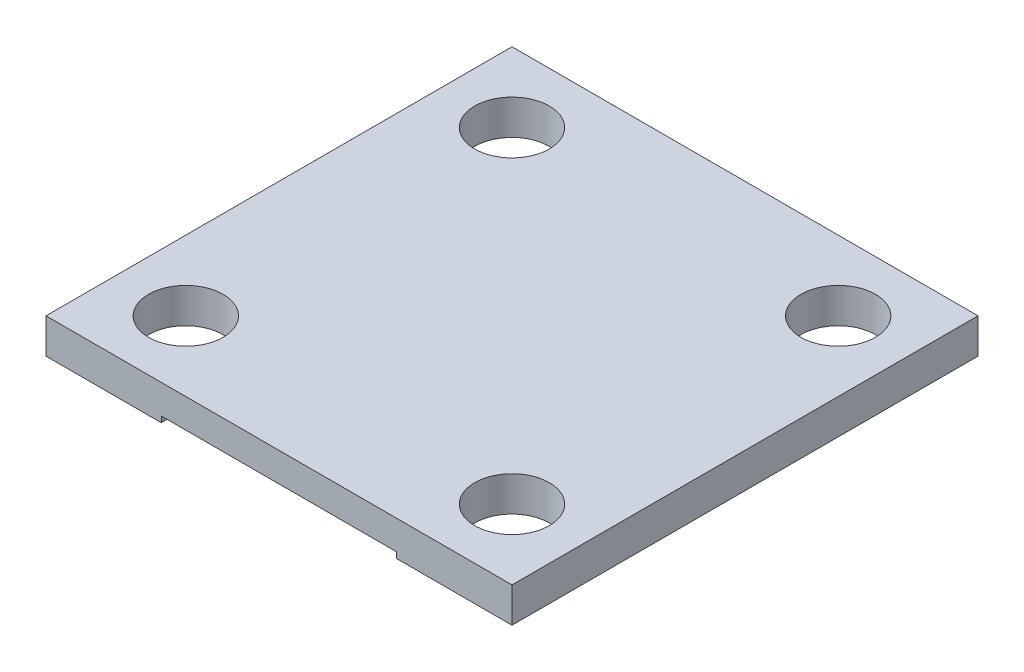
SolidWorks part; units mm, degrees
ref_plane "前视基准面" through (0, 0, 0) normal (0, 0, 1) x (1, 0, 0)
ref_plane "上视基准面" through (0, 0, 0) normal (0, 1, 0) x (1, 0, 0)
ref_plane "右视基准面" through (0, 0, 0) normal (1, 0, 0) x (0, 0, -1)
ref_plane "基准面4" through (0, 0, 0) normal (0, -1, 0) x (1, 0, 0)
sketch "草图1" plane through (0, 0, 0) normal (0, -1, 0) x (1, 0, 0)
  line L0 (10, -10) -> (10, 10)
  line L1 (10, 10) -> (-10, 10)
  line L2 (-10, 10) -> (-10, -10)
  line L3 (-10, -10) -> (10, -10)
extrude "凸台-拉伸1" add sketch "草图1" against normal blind 1.5
sketch "草图2" plane through (0, 0, 0) normal (0, -1, 0) x (1, 0, 0)
  line L0 (-5.05, 10) -> (-5.05, -7.5)
  line L1 (-5.05, -7.5) -> (5.05, -7.5)
  line L2 (5.05, -7.5) -> (5.05, 10)
  line L3 (5.05, 10) -> (-5.05, 10)
extrude "切除-拉伸1" cut sketch "草图2" against normal blind 0.25
hole_wizard "Ø3.2 (3.2) 直径孔1" positions "草图4" profile "草图3" hole size "Ø3.2" standard "ANSI Metric"
sketch "草图4" plane through (0, 1.5, 0) normal (0, 1, 0) x (1, 0, 0)
  point P0 (-7, -7)
  point P1 (7, 7)
sketch "草图3" plane through (-7, 1.5, 7) normal (1, 0, 0) x (0, 0, 1)
  line L0 (0, 0) -> (0, 1.5)
  line L1 (0, 1.5) -> (1.6, 1.5)
  line L2 (1.6, 1.5) -> (1.6, 0)
  line L5 (1.6, 0) -> (0, 0)
  line L11 (0, -6.35) -> (0, 107.95) construction
  dimension "通孔孔直径" = 3.2
  dimension "通孔孔深度" = 1.5
hole_wizard "Ø3.2 (3.2) 直径孔2" positions "草图6" profile "草图5" hole size "Ø3.2" standard "ANSI Metric"
sketch "草图6" plane through (0, 0, 0) normal (0, -1, 0) x (-1, 0, 0)
  point P0 (-7, -7)
  point P1 (7, 7)
sketch "草图5" plane through (7, 0, 7) normal (1, 0, 0) x (0, 0, -1)
  line L0 (0, 0) -> (0, 1.5)
  line L1 (0, 1.5) -> (1.6, 1.5)
  line L2 (1.6, 1.5) -> (1.6, 0)
  line L5 (1.6, 0) -> (0, 0)
  line L11 (0, -6.35) -> (0, 107.95) construction
  dimension "通孔孔直径" = 3.2
  dimension "通孔孔深度" = 1.5
